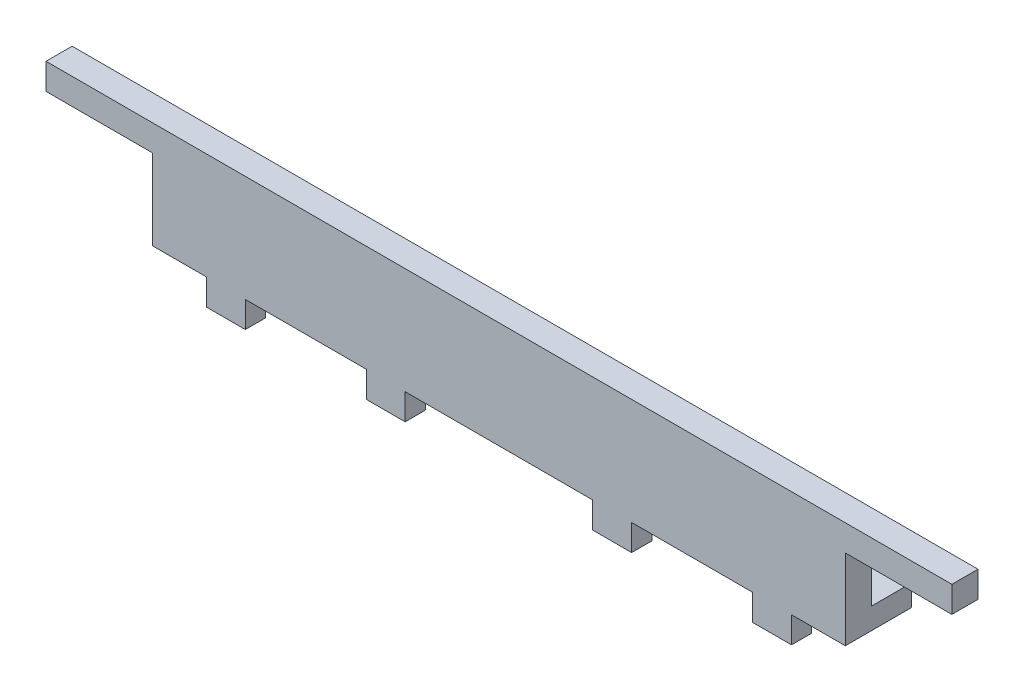
SolidWorks part; units mm, degrees
ref_plane "Front Plane" through (0, 0, 0) normal (0, 0, 1) x (1, 0, 0)
ref_plane "Top Plane" through (0, 0, 0) normal (0, 1, 0) x (1, 0, 0)
ref_plane "Right Plane" through (0, 0, 0) normal (1, 0, 0) x (0, 0, -1)
sketch "Sketch1" plane through (0, 0, 0) normal (0, 0, 1) x (1, 0, 0)
  line L1 (-57.5839, 31.264) -> (72.4161, 31.264)
  line L2 (-57.5839, 31.264) -> (-57.5839, 11.264)
  line L3 (-57.5839, 11.264) -> (72.4161, 11.264)
  line L4 (72.4161, 31.264) -> (72.4161, 11.264)
  dimension "D1" = 130
  dimension "D2" = 20
extrude "Boss-Extrude1" add sketch "Sketch1" along normal blind 4.9
ref_plane "Plane1" through (7.4161, 0, 0) normal (-1, 0, 0) x (0, 0, 1)
sketch "Sketch3" plane through (72.4161, 0, 0) normal (1, 0, 0) x (0, 0, -1)
  line L0 (0, 11.264) -> (0, 31.264) construction
  line L1 (-4.9, 31.264) -> (0, 31.264)
  line L2 (-4.9, 31.264) -> (-4.9, 26.364)
  line L3 (-4.9, 26.364) -> (0, 26.364)
  line L4 (0, 31.264) -> (0, 26.364)
  dimension "D1" = 4.9
extrude "Boss-Extrude2" add sketch "Sketch3" along normal blind 20
mirror "Mirror1" about plane through (7.4161, 0, 0) normal (-1, 0, 0) of "Boss-Extrude2", "Boss-Extrude1"
sketch "Sketch4" plane through (0, 0, 0) normal (0, 0, -1) x (-1, 0, 0)
  line L0 (57.5839, 26.364) -> (57.5839, 11.264) construction
  line L1 (-72.4161, 11.264) -> (57.5839, 11.264)
  line L2 (-72.4161, 11.264) -> (-72.4161, 15.264)
  line L3 (-72.4161, 15.264) -> (57.5839, 15.264)
  line L4 (57.5839, 11.264) -> (57.5839, 15.264)
  dimension "D1" = 4
extrude "Boss-Extrude3" add sketch "Sketch4" along normal blind 7.5
sketch "Sketch5" plane through (0, 11.264, 0) normal (0, -1, 0) x (1, 0, 0)
  line L0 (-57.5839, 4.9) -> (72.4161, 4.9) construction
  line L1 (32.3161, 4.9) -> (25.0161, 4.9)
  line L2 (32.3161, 4.9) -> (32.3161, 1.1)
  line L3 (32.3161, 1.1) -> (25.0161, 1.1)
  line L4 (25.0161, 4.9) -> (25.0161, 1.1)
  line L5 (72.4161, 4.9) -> (72.4161, -7.5) construction
  dimension "D1" = 3.8
  dimension "D2" = 7.3
  dimension "D3" = 40.1
extrude "Boss-Extrude4" add sketch "Sketch5" along normal blind 4.9
mirror "Mirror2" about plane through (7.4161, 0, 0) normal (-1, 0, 0) of "Boss-Extrude4"
sketch "Sketch6" plane through (0, 11.264, 0) normal (0, -1, 0) x (1, 0, 0)
  line L0 (32.3161, 4.9) -> (72.4161, 4.9) construction
  line L1 (62.3161, 4.9) -> (55.0161, 4.9)
  line L2 (62.3161, 4.9) -> (62.3161, 1.1)
  line L3 (62.3161, 1.1) -> (55.0161, 1.1)
  line L4 (55.0161, 4.9) -> (55.0161, 1.1)
  line L5 (72.4161, 4.9) -> (72.4161, -7.5) construction
  dimension "D1" = 7.3
  dimension "D2" = 3.8
  dimension "D3" = 10.1
extrude "Boss-Extrude5" add sketch "Sketch6" along normal blind 4.9
mirror "Mirror3" about plane through (7.4161, 0, 0) normal (-1, 0, 0) of "Boss-Extrude5"
